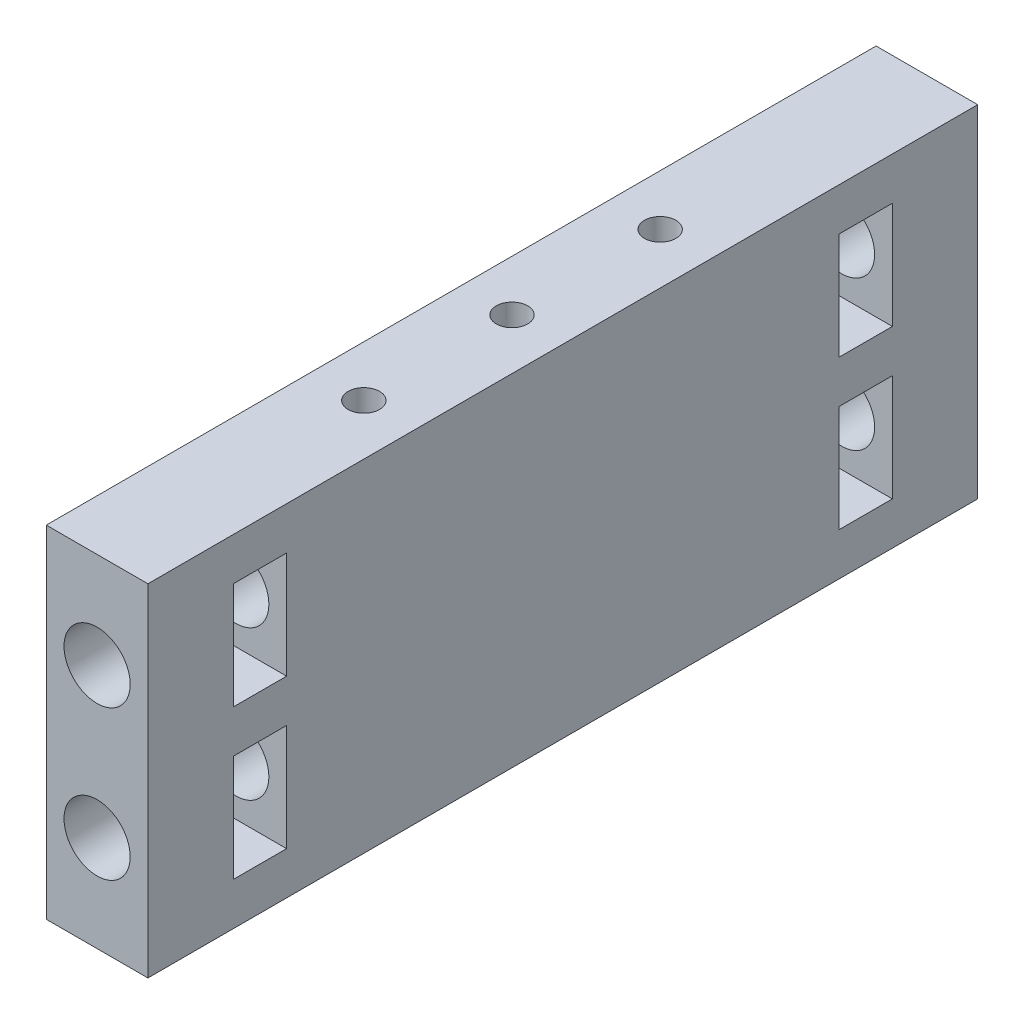
SolidWorks part; units mm, degrees
material "PE High Density"
ref_plane "Front Plane" through (0, 0, 0) normal (0, 0, 1) x (1, 0, 0)
ref_plane "Top Plane" through (0, 0, 0) normal (0, 1, 0) x (1, 0, 0)
ref_plane "Right Plane" through (0, 0, 0) normal (1, 0, 0) x (0, 0, -1)
sketch "Sketch1" plane through (0, 0, 0) normal (0, 0, 1) x (1, 0, 0)
  line L0 (54.75, -16) -> (54.75, 16) construction
  line L1 (64.275, 16) -> (64.275, -16) construction
  line L2 (54.75, -16) -> (54.75, 16)
  line L3 (64.275, 16) -> (64.275, -16)
  line L4 (64.275, 16) -> (54.75, 16)
  line L5 (64.275, -16) -> (54.75, -16)
extrude "Boss-Extrude1" add sketch "Sketch1" along normal up to surface (77.775 mm away)
ref_plane "Vertical Midplane" through (0, 0, 38.8875) normal (0, 0, 1) x (1, 0, 0)
sketch "Sketch2" plane through (64.275, 0, 0) normal (1, 0, 0) x (0, 0, -1)
  line L0 (-87.3, 7) -> (-62.3, 7) construction
  line L1 (-87.3, 10) -> (-62.3, 10) construction
  line L2 (-87.3, 10) -> (-87.3, 4) construction
  line L3 (-87.3, 4) -> (-62.3, 4) construction
  line L4 (-62.3, 10) -> (-62.3, 4) construction
  line L5 (-69.775, 2) -> (-64.775, 2)
  line L6 (-69.775, 2) -> (-69.775, 12)
  line L7 (-69.775, 12) -> (-64.775, 12)
  line L8 (-64.775, 2) -> (-64.775, 12)
  line L9 (-69.775, 2) -> (-64.775, 12) construction
  line L10 (-69.775, 12) -> (-64.775, 2) construction
  line L11 (-77.775, 16) -> (-77.775, -16) construction
  line L12 (-77.775, 16) -> (0, 16) construction
  point P4 (-67.275, 7)
  point P13 (-67.275, 12)
  dimension "D1" = 10
  dimension "D2" = 5
  dimension "D3" = 25
  dimension "D4" = 6
  dimension "D5" = 9.525
  dimension "D6" = 4
  dimension "D7" = 8
extrude "Nut Slot" cut sketch "Sketch2" against normal through all
sketch "Sketch3" plane through (0, 0, 77.775) normal (0, 0, 1) x (1, 0, 0)
  line L0 (64.275, 2) -> (54.75, 12) construction
  line L4 (64.275, 2) -> (64.275, 12)
  line L5 (54.75, 2) -> (64.275, 2)
  line L6 (54.75, 12) -> (54.75, 2)
  line L7 (64.275, 12) -> (54.75, 12)
  line L8 (64.275, 2) -> (64.275, 12) construction
  line L9 (54.75, 2) -> (64.275, 2) construction
  line L10 (54.75, 12) -> (54.75, 2) construction
  line L11 (64.275, 12) -> (54.75, 12) construction
  circle A0 centre (59.5125, 7) radius 3.1
  dimension "D2" = 6.2
  dimension "D1" = 0
extrude "M6 Drill" cut sketch "Sketch3" against normal blind 27 from offset 9.525
mirror "Mirror1" about plane through (0, 0, 0) normal (0, 1, 0) of "M6 Drill", "Nut Slot"
mirror "Mirror2" about plane through (0, 0, 38.8875) normal (0, 0, 1) of "Mirror1", "Nut Slot", "M6 Drill"
sketch "Sketch4" plane through (0, -16, 0) normal (0, -1, 0) x (1, 0, 0)
  line L0 (59.5125, 77.775) -> (59.5125, 0) construction
  line L1 (64.275, 77.775) -> (54.75, 77.775) construction
  line L2 (54.75, 0) -> (64.275, 0) construction
  line L3 (59.5125, 52.775) -> (59.5125, 25) construction
  point P6 (59.5125, 52.775)
  point P12 (59.5125, 38.8875)
  dimension "D1" = 77.775
  dimension "D2" = 25
  dimension "D3" = 27.775
hole_wizard "#32 (0.116) Diameter Hole1" positions "Sketch5" profile "Sketch7" hole size "#32" standard "ANSI Inch"
sketch "Sketch5" plane through (0, -16, 0) normal (0, -1, 0) x (-1, 0, 0)
  point P0 (-59.5125, -52.775)
sketch "Sketch7" plane through (59.5125, -16, 52.775) normal (1, 0, 0) x (0, 0, -1)
  line L0 (0, 0) -> (0, 10.4102)
  line L1 (0, 10.4102) -> (1.4732, 9.525)
  line L2 (1.4732, 9.525) -> (1.4732, 0)
  line L5 (1.4732, 0) -> (0, 0)
  line L10 (0, 10.4102) -> (-1.4732, 9.525) construction
  line L11 (0, -6.35) -> (0, 107.95) construction
  dimension "Hole Dia." = 2.9464
  dimension "Hole Depth" = 9.525
  dimension "Drill Angle" = 118
pattern_linear "LPattern1" count 3 spacing 13.8875 along (0, 0, -1) of "#32 (0.116) Diameter Hole1"
mirror "Mirror3" about plane through (0, 0, 0) normal (0, 1, 0) of "LPattern1", "#32 (0.116) Diameter Hole1"
sketch "Sketch8" [suppressed] plane through (64.275, 0, 0) normal (1, 0, 0) x (0, 0, -1)
  line L0 (-77.775, -16) -> (0, -16) construction
  line L1 (-49.775, 13) -> (-41.8875, 13)
  line L2 (-49.775, 13) -> (-49.775, 1.5)
  line L3 (-49.775, 1.5) -> (-41.8875, 1.5)
  line L4 (-41.8875, 13) -> (-41.8875, 1.5)
  line L5 (-77.775, -16) -> (0, -16) construction
  line L6 (-38.8875, -16) -> (-38.8875, 16) construction
  line L7 (-77.775, 16) -> (0, 16) construction
  line L8 (-52.775, -16) -> (-52.775, 16) construction
  line L9 (-41.8875, 7.25) -> (-38.8875, 7.25) construction
  line L10 (-49.775, 7.25) -> (-52.775, 7.25) construction
  line L11 (-45.8312, 13) -> (-45.8312, 16) construction
  line L12 (-38.8875, 0) -> (-52.775, 0) construction
  line L13 (-45.8312, 0) -> (-45.8312, 1.5) construction
  point P5 (-52.775, -16)
  dimension "D1" = 3
  dimension "D2" = 1.5
extrude "Cut-Extrude1" [suppressed] cut sketch "Sketch8" against normal through all
fillet "Fillet1" [suppressed] radius 3
mirror "Mirror6" [suppressed] about plane through (0, 0, 0) normal (0, 1, 0)
sketch "Sketch9" [suppressed] plane through (64.275, 0, 0) normal (1, 0, 0) x (0, 0, -1)
  line L0 (-52.775, 5) -> (-52.775, -5)
  line L1 (-52.775, -5) -> (-61.4353, 0)
  line L2 (-61.4353, 0) -> (-52.775, 5)
  line L3 (-52.775, -16) -> (-52.775, 16) construction
  line L4 (-52.775, -16) -> (-52.775, 16) construction
  line L5 (-52.775, 0) -> (-61.4353, 0) construction
  line L6 (-49.775, 13) -> (-49.775, 1.5) construction
  dimension "D1" = 3
  dimension "D2" = 10
extrude "Cut-Extrude2" [suppressed] cut sketch "Sketch9" against normal through all
fillet "Fillet2" [suppressed] radius 1.5
mirror "Mirror7" [suppressed] about plane through (0, 0, 38.8875) normal (0, 0, 1)
equation "\"D3@LPattern1\"=\"D3@Sketch4\"/2"
equation "\"D2@Sketch8\"=\"D1@Sketch8\"/2"
